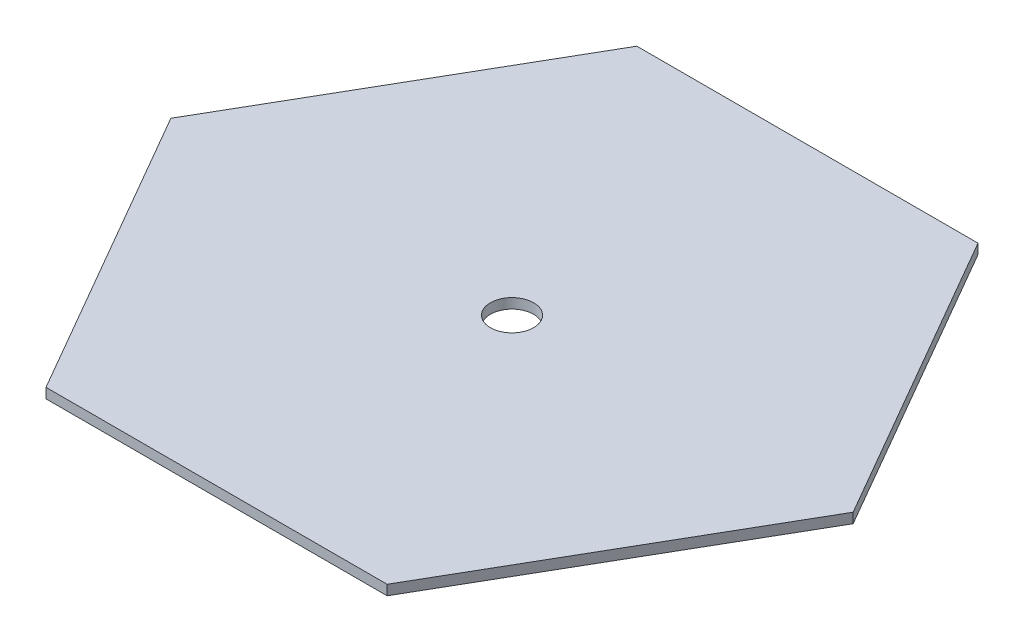
SolidWorks part; units mm, degrees
ref_plane "Front Plane" through (0, 0, 0) normal (0, 0, 1) x (1, 0, 0)
ref_plane "Top Plane" through (0, 0, 0) normal (0, 1, 0) x (1, 0, 0)
ref_plane "Right Plane" through (0, 0, 0) normal (1, 0, 0) x (0, 0, -1)
sketch "Sketch1" plane through (0, 0, 0) normal (0, 1, 0) x (1, 0, 0)
  line L1 (85.25, -147.6573) -> (170.5, 0)
  line L2 (170.5, 0) -> (85.25, 147.6573)
  line L3 (85.25, 147.6573) -> (-85.25, 147.6573)
  line L4 (-85.25, 147.6573) -> (-170.5, 0)
  line L5 (-170.5, 0) -> (-85.25, -147.6573)
  line L6 (-85.25, -147.6573) -> (85.25, -147.6573)
  circle A0 centre (0, 0) radius 147.6573 construction
  circle A1 centre (0, 0) radius 10.81
  dimension "D1" = 170.5
extrude "Boss-Extrude1" add sketch "Sketch1" along normal blind 5
equation "\"side\"= 170.5"
equation "\"D1@Sketch1\"=\"side\""
